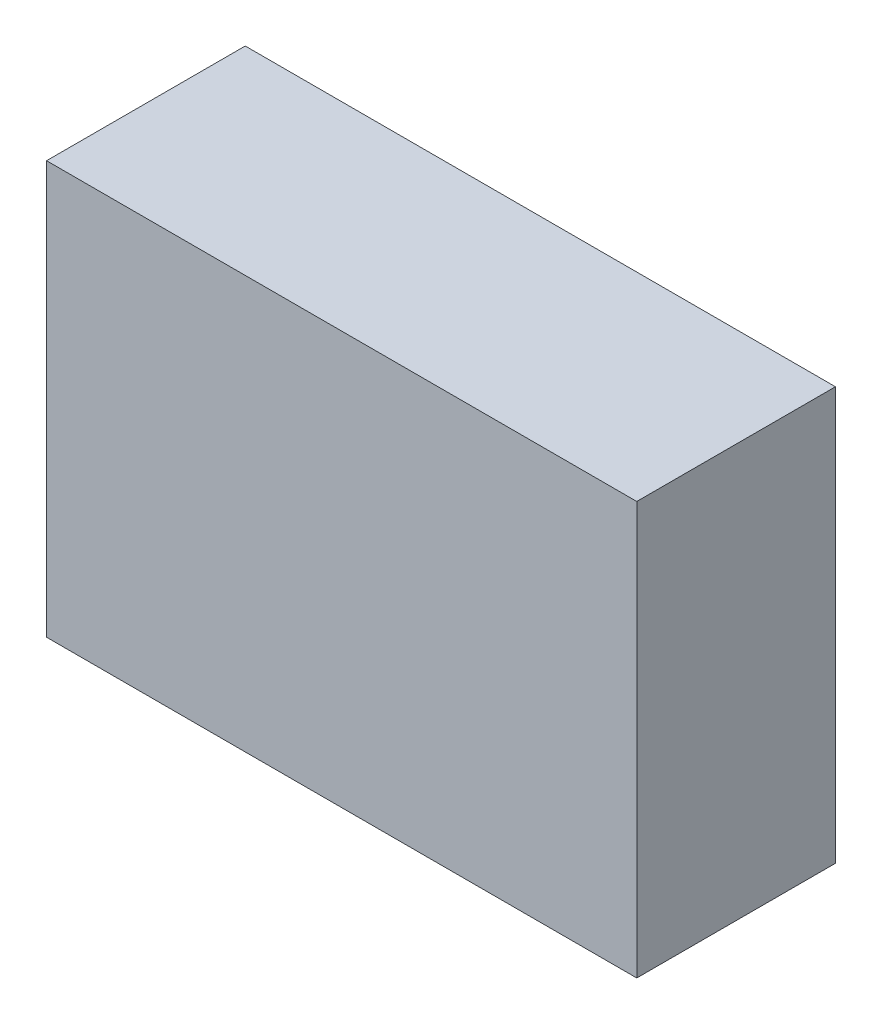
SolidWorks part; units mm, degrees
ref_plane "Front Plane" through (0, 0, 0) normal (0, 0, 1) x (1, 0, 0)
ref_plane "Top Plane" through (0, 0, 0) normal (0, 1, 0) x (1, 0, 0)
ref_plane "Right Plane" through (0, 0, 0) normal (1, 0, 0) x (0, 0, -1)
sketch "Sketch1" plane through (0, 0, 0) normal (0, 0, 1) x (1, 0, 0)
  line L1 (0, 0) -> (8.08, 0)
  line L2 (0, 0) -> (0, 5.65)
  line L3 (0, 5.65) -> (8.08, 5.65)
  line L4 (8.08, 0) -> (8.08, 5.65)
  dimension "D1" = 8.08
  dimension "D2" = 5.65
extrude "Boss-Extrude1" add sketch "Sketch1" along normal blind 2.72 contours L1 L4 L3 L2
sketch "Sketch2" plane through (0, 0, 0) normal (0, -1, 0) x (1, 0, 0)
  line L0 (0.54, 2.3) -> (7.54, 2.3)
  line L1 (7.54, 2.3) -> (6.425, 0.42)
  line L2 (6.425, 0.42) -> (1.655, 0.42)
  line L3 (1.655, 0.42) -> (0.54, 2.3)
  line L4 (0, 1.36) -> (8.08, 1.36) construction
  line L5 (0, 2.72) -> (0, 0) construction
  line L6 (8.08, 2.72) -> (8.08, 0) construction
  line L7 (4.04, 0) -> (4.04, 2.72) construction
  line L8 (0, 0) -> (8.08, 0) construction
  line L9 (0, 2.72) -> (8.08, 2.72) construction
  dimension "D1" = 1.88
  dimension "D2" = 7
  dimension "D3" = 4.77
extrude "Cut-Extrude1" cut sketch "Sketch2" against normal blind 4
sketch "Sketch3" plane through (0, 0, 0) normal (0, -1, 0) x (1, 0, 0)
  line L0 (0, 1.36) -> (8.08, 1.36) construction
  line L1 (0, 2.72) -> (0, 0) construction
  line L2 (8.08, 2.72) -> (8.08, 0) construction
  line L3 (4.04, 2.72) -> (4.04, 0) construction
  line L4 (0, 2.72) -> (8.08, 2.72) construction
  line L5 (0, 0) -> (8.08, 0) construction
